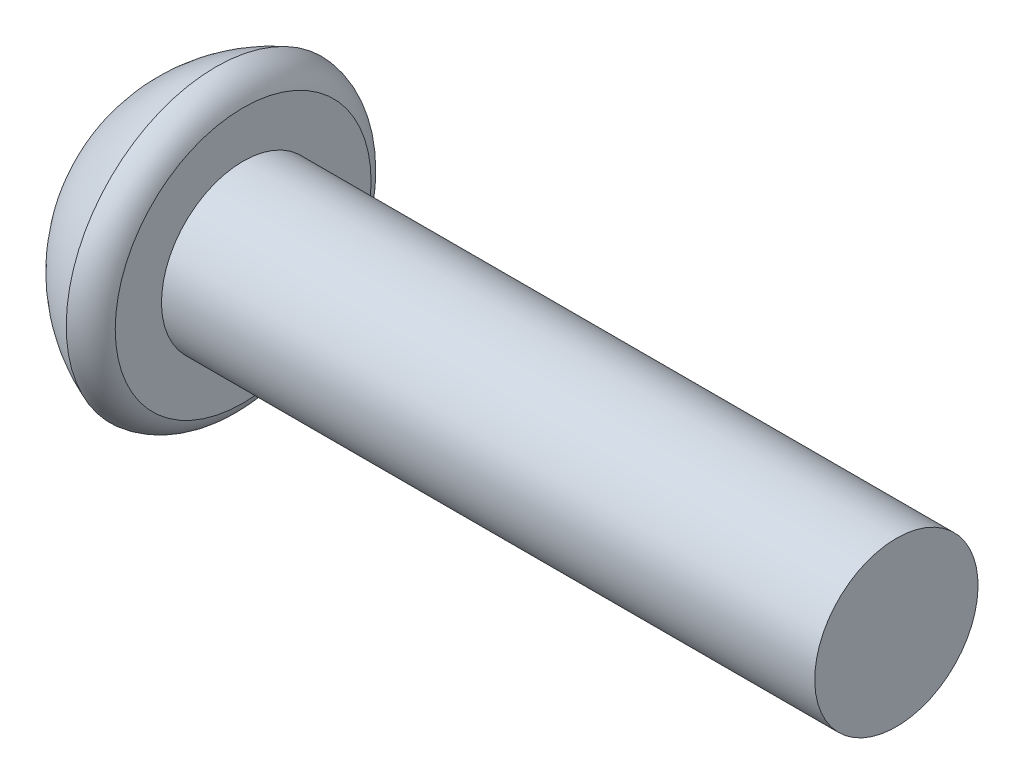
SolidWorks part; units mm, degrees
material "AISI 1020"
ref_plane "Front Plane" through (0, 0, 0) normal (0, 0, 1) x (1, 0, 0)
ref_plane "Top Plane" through (0, 0, 0) normal (0, 1, 0) x (1, 0, 0)
ref_plane "Right Plane" through (0, 0, 0) normal (1, 0, 0) x (0, 0, -1)
sketch "Sketch1" plane through (0, 0, 0) normal (0, 0, 1) x (1, 0, 0)
  line L0 (0, 0) -> (12, 0)
  line L1 (12, 0) -> (12, -1.5)
  line L2 (12, -1.5) -> (-2, -1.5)
  line L5 (0, 0.85) -> (0, 0)
  line L6 (-2, -1.5) -> (-2, 0)
  line L7 (-0.5, -1.5) -> (-0.5, 1.25) construction
  arc A1 (-2, 0) -> (-0.5, 1.25) centre (0.5389, -1.5217) cw
  arc A2 (-0.5, 1.25) -> (0, 0.85) centre (-0.567, 0.6538) cw
  dimension "D4" = 0.4
  dimension "D8" = 2.96
  dimension "D9" = 0.6
  dimension "D1" = 1.5
  dimension "D2" = 2
  dimension "D3" = 2.75
  dimension "D5" = 12
  dimension "D6" = 0.5
  dimension "D7" = 1.5
revolve "Revolve1" add sketch "Sketch1" angle 360 about L2
cosmetic thread "Cosmetic Thread1" parameters "D2"=2
sketch "Sketch2" plane through (-2, 0, 0) normal (-1, 0, 0) x (0, 0, 1)
  line L1 (0, -0.2298) -> (-1.1, -0.8649)
  line L2 (-1.1, -0.8649) -> (-1.1, -2.1351)
  line L3 (-1.1, -2.1351) -> (0, -2.7702)
  line L4 (0, -2.7702) -> (1.1, -2.1351)
  line L5 (1.1, -2.1351) -> (1.1, -0.8649)
  line L6 (1.1, -0.8649) -> (0, -0.2298)
  circle A0 centre (0, -1.5) radius 1.1 construction
  dimension "D1" = 2.2
extrude "Cut-Extrude1" cut sketch "Sketch2" against normal blind 1.5
